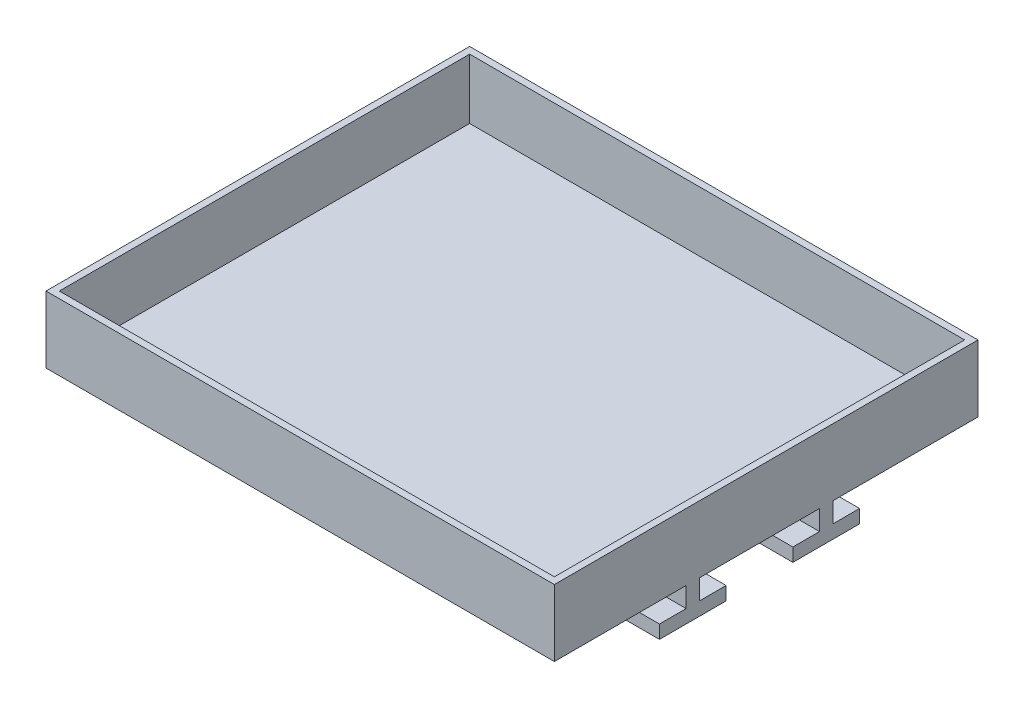
SolidWorks part; units mm, degrees
ref_plane "Front Plane" through (0, 0, 0) normal (0, 0, 1) x (1, 0, 0)
ref_plane "Top Plane" through (0, 0, 0) normal (0, 1, 0) x (1, 0, 0)
ref_plane "Right Plane" through (0, 0, 0) normal (1, 0, 0) x (0, 0, -1)
sketch "Sketch1" plane through (0, 0, 0) normal (0, 1, 0) x (1, 0, 0)
  line L1 (-38.1, 31.75) -> (38.1, 31.75)
  line L2 (-38.1, 31.75) -> (-38.1, -31.75)
  line L3 (-38.1, -31.75) -> (38.1, -31.75)
  line L4 (38.1, 31.75) -> (38.1, -31.75)
  line L5 (-38.1, 31.75) -> (38.1, -31.75) construction
  line L6 (-38.1, -31.75) -> (38.1, 31.75) construction
  point P0 (0, 0)
  dimension "D1" = 76.2
  dimension "D2" = 63.5
extrude "Boss-Extrude1" add sketch "Sketch1" along normal blind 10
shell "Shell1" thickness 1
sketch "Sketch2" plane through (38.1, 0, 0) normal (1, 0, 0) x (0, 0, -1)
  line L0 (-9, 0) -> (9, 0) construction
  line L1 (-31.75, 0) -> (31.75, 0) construction
  line L2 (10, -3) -> (14, -3)
  line L4 (8, -3) -> (8, 0)
  line L5 (8, 0) -> (10, 0)
  line L6 (10, -3) -> (10, 0)
  line L7 (8, -3) -> (10, 0) construction
  line L8 (8, 0) -> (10, -3) construction
  line L9 (4, -5) -> (14, -5)
  line L10 (4, -5) -> (4, -3)
  line L11 (4, -3) -> (8, -3)
  line L12 (14, -5) -> (14, -3)
  line L13 (4, -5) -> (14, -3) construction
  line L14 (4, -3) -> (14, -5) construction
  point P4 (0, 0)
  point P5 (9, -1.5)
  point P11 (9, -4)
  point P16 (9, -5)
  point P17 (0, 0)
  point P18 (10.4006, -3)
  dimension "D1" = 18
  dimension "D2" = 3
  dimension "D3" = 2
  dimension "D4" = 10
  dimension "D5" = 4
extrude "Boss-Extrude2" add sketch "Sketch2" against normal up to surface (76.2 mm away) contours L2 L12 L9 L10 L11 L4 L5 L6 up to face at (-38.1, 5, 0)
pattern_linear "LPattern1" count 2 spacing 20 along (0, 0, 1) of "Boss-Extrude2"
